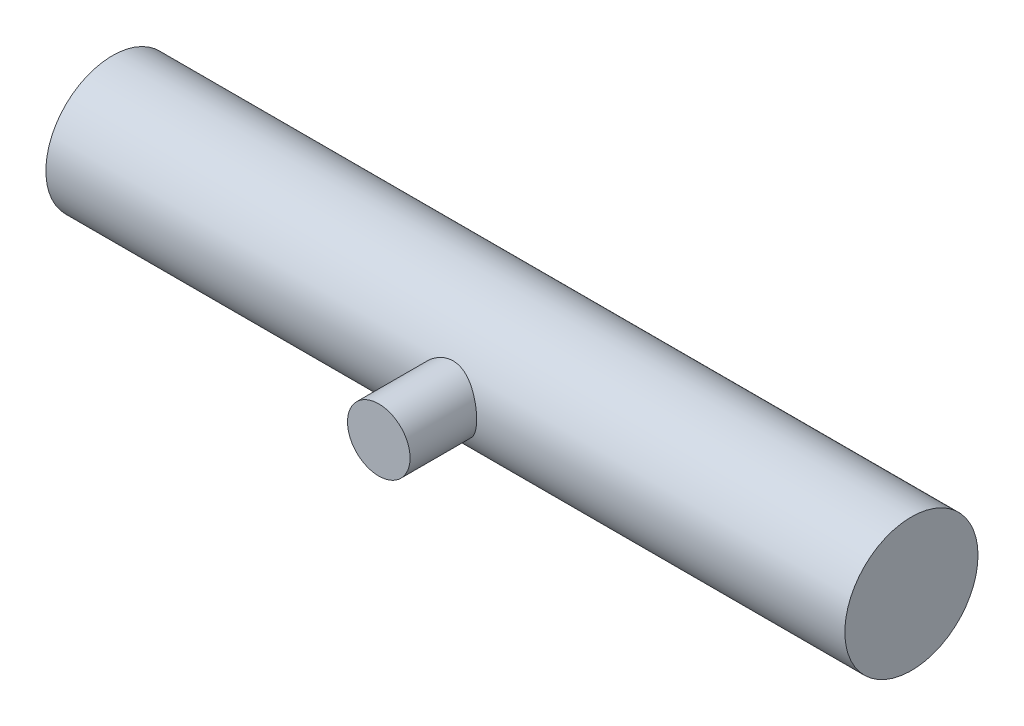
SolidWorks part; units mm, degrees
ref_plane "前视基准面" through (0, 0, 0) normal (0, 0, 1) x (1, 0, 0)
ref_plane "上视基准面" through (0, 0, 0) normal (0, 1, 0) x (1, 0, 0)
ref_plane "右视基准面" through (0, 0, 0) normal (1, 0, 0) x (0, 0, -1)
other "Configuration Table"
sketch "草图1" plane through (0, 0, 0) normal (1, 0, 0) x (0, 0, -1)
  circle A0 centre (0, 0) radius 5
  dimension "D1" = 10
extrude "凸台-拉伸1" add sketch "草图1" along normal mid plane 60
sketch "草图2" plane through (0, 0, 0) normal (0, 0, 1) x (1, 0, 0)
  circle A0 centre (0, 0) radius 2.35
  dimension "D1" = 4.7
extrude "凸台-拉伸2" add sketch "草图2" along normal blind 10
